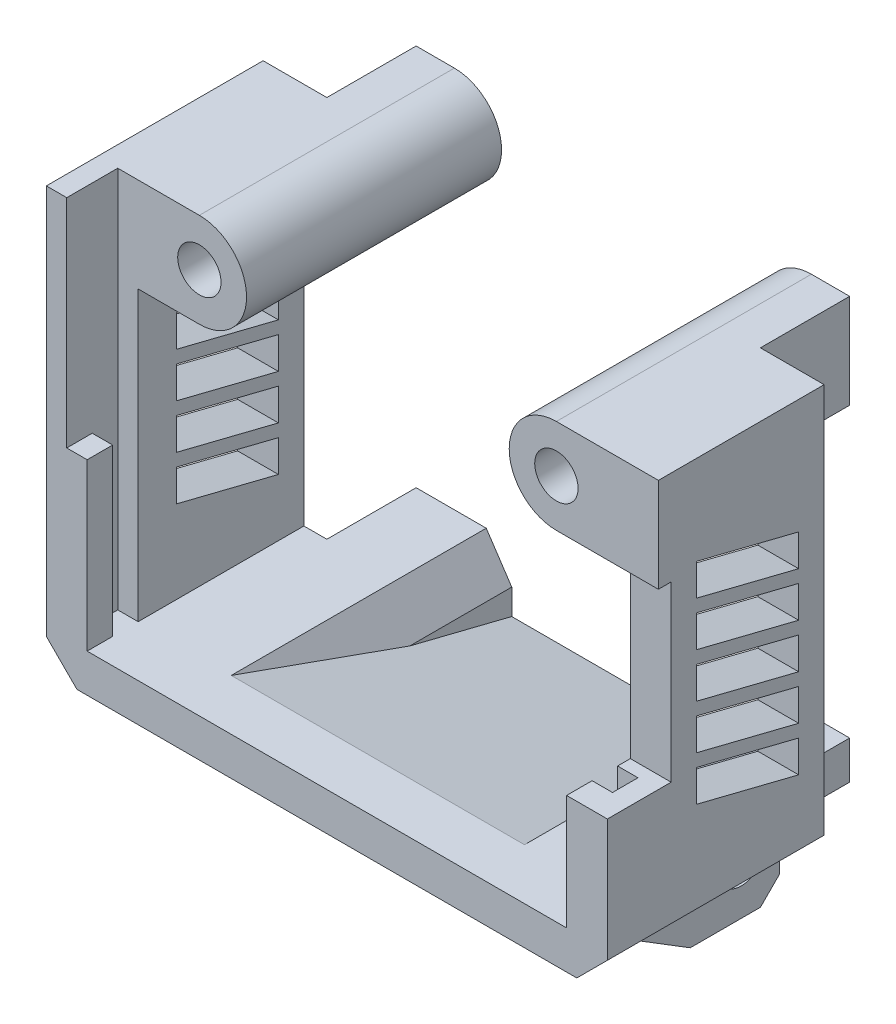
SolidWorks part; units mm, degrees
ref_plane "Спереди" through (0, 0, 0) normal (0, 0, 1) x (1, 0, 0)
ref_plane "Сверху" through (0, 0, 0) normal (0, 1, 0) x (1, 0, 0)
ref_plane "Справа" through (0, 0, 0) normal (1, 0, 0) x (0, 0, -1)
sketch "Эскиз1" plane through (0, 0, 0) normal (0, 0, 1) x (1, 0, 0)
  line L1 (22, 44) -> (-22, 44)
  line L2 (22, 44) -> (22, 10)
  line L3 (22, 10) -> (-22, 10)
  line L4 (-22, 44) -> (-22, 10)
  line L5 (22, 44) -> (-22, 10) construction
  line L6 (22, 10) -> (-22, 44) construction
  point P0 (0, 27)
  dimension "D1" = 10
  dimension "D2" = 44
  dimension "D3" = 44
extrude "Бобышка-Вытянуть1" add sketch "Эскиз1" along normal blind 24
sketch "Эскиз2" plane through (0, 44, 0) normal (0, 1, 0) x (1, 0, 0)
  line L0 (0, 0) -> (0, -24) construction
  line L1 (22, 0) -> (-22, 0) construction
  line L2 (-18.8, 0) -> (18.8, 0)
  line L3 (-18.8, 0) -> (-18.8, -20)
  line L4 (-20.4, -22) -> (-20.4, -20)
  line L5 (18.8, 0) -> (18.8, -20)
  line L6 (-22, -24) -> (-22, 0) construction
  line L7 (22, -24) -> (-22, -24) construction
  line L8 (-18.8, -24) -> (18.8, -24)
  line L9 (-18.8, -24) -> (-18.8, -22)
  line L10 (-18.8, -20) -> (-20.4, -20)
  line L11 (18.8, -24) -> (18.8, -22)
  line L12 (18.8, -22) -> (20.4, -22)
  line L13 (-18.8, -22) -> (-20.4, -22)
  line L14 (18.8, -20) -> (20.4, -20)
  line L15 (20.4, -22) -> (20.4, -20)
  line L16 (22, -24) -> (22, 0) construction
  point P6 (0, 0)
  point P16 (0, -24)
  dimension "D1" = 1.6
  dimension "D2" = 3.2
  dimension "D3" = 2
  dimension "D4" = 20
extrude "Вырез-Вытянуть1" cut sketch "Эскиз2" against normal blind 31
sketch "Эскиз5" plane through (0, 0, 0) normal (0, 0, -1) x (-1, 0, 0)
  line L0 (22, 10) -> (-22, 10) construction
  line L1 (-11.5, 10) -> (11.5, 10)
  line L2 (-11.5, 10) -> (-11.5, -0.5)
  line L3 (-11.5, -0.5) -> (11.5, -0.5)
  line L4 (11.5, 10) -> (11.5, -0.5)
  point P6 (0, -0.5)
  dimension "D1" = 23
  dimension "D2" = 10.5
extrude "Бобышка-Вытянуть4" add sketch "Эскиз5" along normal blind 1 separate body
sketch "Эскиз6" plane through (11.5, 0, 0) normal (1, 0, 0) x (0, 0, -1)
  line L0 (0, -0.5) -> (-7, -0.5)
  line L1 (-24, 10) -> (0, 10)
  line L2 (0, 10) -> (0, -0.5)
  line L3 (-7, -0.5) -> (-24, 10)
  dimension "D1" = 7
extrude "Бобышка-Вытянуть5" add sketch "Эскиз6" against normal up to surface (23 mm away) up to face at (-11.5, 4.75, -0.5)
sketch "Эскиз7" plane through (-11.5, 0, 0) normal (-1, 0, 0) x (0, 0, 1)
  line L1 (24, 10) -> (0, 10) construction
  line L2 (0, 44) -> (0, 10) construction
  circle A0 centre (3, 3.5) radius 1.8
  point P4 (1.9097, 5)
  point P6 (-3.6073, 4.906)
  dimension "D1" = 3.6
  dimension "D2" = 6.5
  dimension "D3" = 3
extrude "Вырез-Вытянуть2" cut sketch "Эскиз7" against normal up to surface (23 mm away) up to face at (11.5, 5.8, 5.8)
ref_plane "Плоскость1" through (-9.5, 0, 0) normal (-1, 0, 0) x (0, 0, 1)
sketch "Эскиз8" plane through (-9.5, 0, 0) normal (-1, 0, 0) x (0, 0, 1)
  line L0 (0, 8) -> (20, 13)
  line L1 (20, 13) -> (0, 13)
  line L2 (0, 13) -> (0, 8)
  point P4 (0, 0)
  point P7 (0, 7.2504)
  point P8 (0, 7.2474)
  dimension "D1" = 5
extrude "Вырез-Вытянуть4" cut sketch "Эскиз8" against normal offset from surface (19 mm away) 2 up to face at (11.5, 1.7, 3)
chamfer "Фаска2" distance 2 distance2 3 1 edges at (9.5, 13, 10)
sketch "Эскиз11" plane through (0, 0, 0) normal (0, 0, -1) x (-1, 0, 0)
  line L0 (-22, 44) -> (-18.8, 44) construction
  line L1 (-14, 43) -> (-18.8, 43)
  line L2 (-18.8, 13) -> (-18.8, 44) construction
  line L3 (-18.8, 43) -> (-18.8, 35.6)
  line L4 (-18.8, 35.6) -> (-14, 35.6)
  line L5 (0, 0) -> (0, 30) construction
  line L6 (18.8, 35.6) -> (14, 35.6)
  line L7 (18.8, 43) -> (18.8, 35.6)
  line L8 (14, 43) -> (18.8, 43)
  circle A0 centre (-14, 39.3) radius 1.7
  arc A1 (-14, 35.6) -> (-14, 43) centre (-14, 39.3) ccw
  arc A2 (14, 35.6) -> (14, 43) centre (14, 39.3) cw
  circle A3 centre (-14, 39.3) radius 3.7 construction
  circle A4 centre (14, 39.3) radius 1.7
  point P11 (-10.3, 30)
  dimension "D1" = 14
  dimension "D3" = 3.4
  dimension "D2" = 4.7
  dimension "D4" = 2
extrude "Бобышка-Вытянуть6" add sketch "Эскиз11" against normal up to surface (20 mm away) up to face at (19.6, 28.5, 20)
sketch "Эскиз13" plane through (-22, 0, 0) normal (-1, 0, 0) x (0, 0, 1)
  line L0 (0, 44) -> (0, 10) construction
  line L1 (9, 34) -> (17, 36)
  line L2 (9, 34) -> (9, 31.5)
  line L3 (9, 31.5) -> (17, 33.5)
  line L4 (17, 36) -> (17, 33.5)
  line L5 (24, 44) -> (0, 44) construction
  line L6 (0, 14) -> (24, 14) construction
  line L7 (24, 44) -> (24, 10) construction
  line L8 (9, 30.5) -> (17, 32.5)
  line L9 (9, 30.5) -> (9, 28)
  line L10 (9, 28) -> (17, 30)
  line L11 (17, 32.5) -> (17, 30)
  line L12 (9, 27) -> (17, 29)
  line L13 (9, 27) -> (9, 24.5)
  line L14 (9, 24.5) -> (17, 26.5)
  line L15 (17, 29) -> (17, 26.5)
  line L16 (9, 23.5) -> (17, 25.5)
  line L17 (9, 23.5) -> (9, 21)
  line L18 (9, 21) -> (17, 23)
  line L19 (17, 25.5) -> (17, 23)
  line L20 (9, 20) -> (17, 22)
  line L21 (9, 20) -> (9, 17.5)
  line L22 (9, 17.5) -> (17, 19.5)
  line L23 (17, 22) -> (17, 19.5)
  dimension "D1" = 2.5
  dimension "D2" = 8
  dimension "D3" = 7
  dimension "D4" = 10
  dimension "D5" = 8
  dimension "D6" = 30
  dimension "D7" = 5
extrude "Вырез-Вытянуть7" cut sketch "Эскиз13" against normal blind 4
mirror "Зеркальное отражение1" about plane through (0, 0, 0) normal (1, 0, 0) of "Вырез-Вытянуть7"
chamfer "Фаска3" distance 2.4 angle 45 2 edges at (-22, 10, 12) (22, 10, 12)
sketch "Эскиз14" plane through (0, 44, 0) normal (0, 1, 0) x (1, 0, 0)
  line L0 (22, -24) -> (18.8, -24) construction
  line L1 (-20.4, -20) -> (20.4, -20)
  line L2 (-20.4, -20) -> (-20.4, -24)
  line L3 (-20.4, -24) -> (20.4, -24)
  line L4 (20.4, -20) -> (20.4, -24)
extrude "Вырез-Вытянуть8" cut sketch "Эскиз14" against normal blind 18
sketch "Эскиз15" plane through (0, 0, 0) normal (0, 0, -1) x (-1, 0, 0)
  line L0 (-22, 12.4) -> (-22, 44) construction
  line L1 (-22, 43) -> (22, 43)
  line L2 (-22, 43) -> (-22, 44)
  line L3 (-22, 44) -> (22, 44)
  line L4 (22, 43) -> (22, 44)
  line L5 (18.8, 44) -> (22, 44) construction
extrude "Вырез-Вытянуть9" cut sketch "Эскиз15" against normal up to surface (24 mm away) up to face at (0, 23.175, 24)
sketch "Эскиз16" plane through (0, 0, 24) normal (0, 0, 1) x (1, 0, 0)
  line L0 (18.8, 13) -> (18.8, 26) construction
  line L1 (18.8, 22) -> (22, 22)
  line L2 (18.8, 22) -> (18.8, 35.6)
  line L3 (18.8, 35.6) -> (22, 35.6)
  line L4 (22, 22) -> (22, 35.6)
  line L5 (22, 12.4) -> (22, 43) construction
  line L6 (11.5, 10) -> (19.6, 10) construction
  line L7 (14, 35.6) -> (18.8, 35.6) construction
  point P10 (15.55, 10)
  dimension "D1" = 12
extrude "Вырез-Вытянуть10" cut sketch "Эскиз16" against normal blind 5
sketch "Эскиз17" plane through (0, 43, 0) normal (0, 1, 0) x (1, 0, 0)
  line L1 (20.4, -20) -> (22, -20)
  line L2 (20.4, -20) -> (20.4, -24)
  line L3 (20.4, -24) -> (22, -24)
  line L4 (22, -20) -> (22, -24)
extrude "Вырез-Вытянуть11" cut sketch "Эскиз17" against normal up to surface (7.4 mm away) up to face at (18.6667, 35.6, 15.9)
sketch "Эскиз18" plane through (0, 0, 0) normal (0, 0, -1) x (-1, 0, 0)
  line L0 (-14, 43) -> (-22, 43) construction
  line L2 (0, 0) -> (0, 43) construction
  line L4 (-22, 43) -> (-17, 43)
  line L5 (-17, 43) -> (-17, 10)
  line L6 (19.6, 10) -> (11.5, 10) construction
  line L7 (-22, 43) -> (-22, 12.4)
  line L8 (-19.6, 10) -> (-17, 10)
  line L10 (-11.5, 10) -> (-19.6, 10) construction
  line L11 (-22, 12.4) -> (-19.6, 10)
  line L12 (22, 12.4) -> (19.6, 10)
  line L13 (17, 43) -> (17, 10)
  line L14 (19.6, 10) -> (17, 10)
  line L15 (22, 43) -> (22, 12.4)
  line L16 (22, 43) -> (17, 43)
  point P5 (17, 10)
  point P10 (0, 33.1668)
  point P11 (0, 0)
  point P12 (0, 43)
  dimension "D1" = 5
extrude "Вырез-Вытянуть12" cut sketch "Эскиз18" against normal blind 7
sketch "Эскиз19" plane through (-11.5, 0, 0) normal (-1, 0, 0) x (0, 0, 1)
  line L1 (0, 10) -> (-1, 10)
  line L2 (0, 10) -> (0, -0.5)
  line L3 (0, -0.5) -> (-1, -0.5)
  line L4 (-1, 10) -> (-1, -0.5)
extrude "Вырез-Вытянуть13" cut sketch "Эскиз19" against normal up to surface (23 mm away) up to face at (11.5, 1.7, 3)
chamfer "Фаска4" distance 1.5 angle 45 1 edges at (0, -0.5, 0)
chamfer "Фаска5" distance 3 distance2 2 1 edges at (-9.5, 13, 10)
